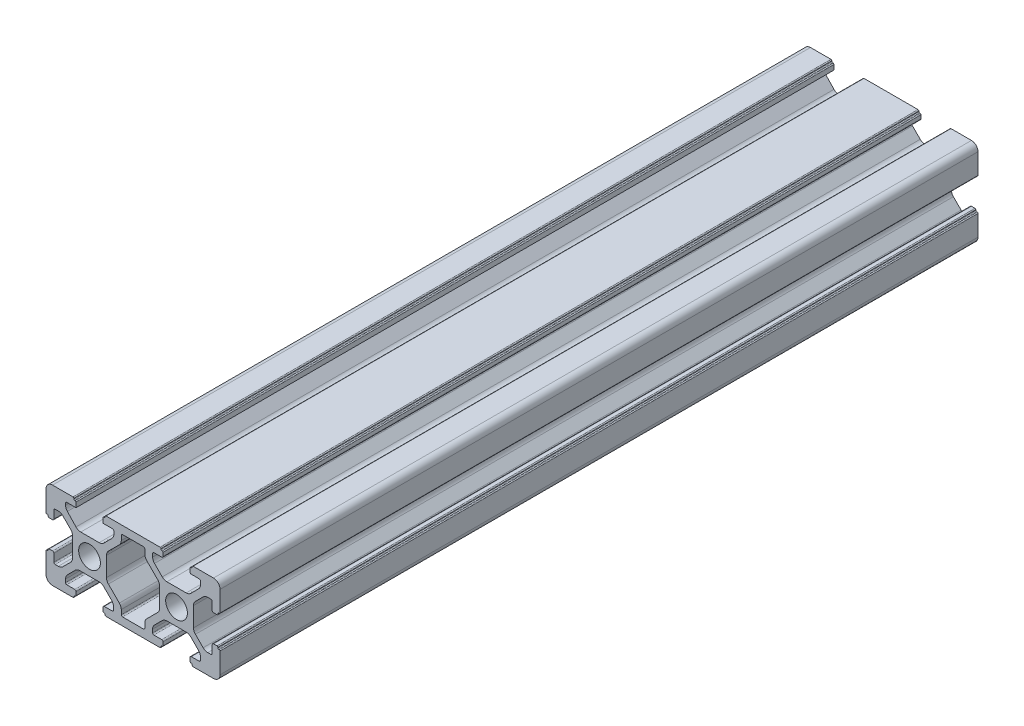
SolidWorks part; units mm, degrees
material "6063-O"
ref_plane "Front Plane" through (0, 0, 0) normal (0, 0, 1) x (1, 0, 0)
ref_plane "Top Plane" through (0, 0, 0) normal (0, 1, 0) x (1, 0, 0)
ref_plane "Right Plane" through (0, 0, 0) normal (1, 0, 0) x (0, 0, -1)
sketch "Sketch1" plane through (0, 0, 0) normal (0, 0, 1) x (1, 0, 0)
  line L0 (1.5, 0) -> (6.2, 0)
  line L1 (40, 1.5) -> (40, 6.2)
  line L2 (38.5, 20) -> (33.8, 20)
  line L3 (0, 18.5) -> (0, 13.8)
  line L4 (17.6, 1.8) -> (22.4, 1.8)
  line L5 (32.218, 13.9) -> (27.782, 13.9)
  line L6 (26.1, 12.218) -> (26.1, 7.782)
  line L7 (17.6, 18.2) -> (22.4, 18.2)
  line L8 (12.218, 13.9) -> (7.9864, 13.9)
  line L9 (6.1, 12.218) -> (6.1, 7.782)
  line L10 (7.782, 6.1) -> (12.218, 6.1)
  line L11 (13.9, 7.782) -> (13.9, 12.218)
  line L12 (27.782, 6.1) -> (32.218, 6.1)
  line L13 (33.9, 7.782) -> (33.9, 12.218)
  line L14 (26.7213, 14.3393) -> (24.9393, 16.1213)
  line L15 (33.2787, 14.3393) -> (35.0607, 16.1213)
  line L16 (34.3393, 13.2787) -> (36.1213, 15.0607)
  line L17 (25.6607, 6.7213) -> (23.1393, 4.2)
  line L18 (15.2, 1.8) -> (13.4, 1.8)
  line L19 (26.7213, 5.6607) -> (24.9393, 3.8787)
  line L20 (24.8, 1.8) -> (26.6, 1.8)
  line L21 (15.3, 18.2) -> (13.1, 18.2)
  line L22 (13.2787, 14.3393) -> (15.1607, 16.2213)
  line L23 (14.3393, 13.2787) -> (16.8607, 15.8)
  line L24 (5.6607, 6.7213) -> (3.8787, 4.9393)
  line L25 (6.7213, 5.6607) -> (4.9393, 3.8787)
  line L26 (6.897, 14.3689) -> (4.9106, 16.4674)
  line L27 (5.6607, 13.2787) -> (3.8787, 15.0607)
  line L28 (14.3393, 6.7213) -> (16.8607, 4.2)
  line L29 (13.2787, 5.6607) -> (15.0607, 3.8787)
  line L30 (24.8, 18.2) -> (26.6, 18.2)
  line L31 (25.6607, 13.2787) -> (23.1393, 15.8)
  line L32 (34.3393, 6.7213) -> (36.1213, 4.9393)
  line L33 (33.2787, 5.6607) -> (35.0607, 3.8787)
  line L34 (1.8, 15.2) -> (1.8, 13.4)
  line L35 (24.5, 2.1) -> (24.5, 2.818)
  line L36 (4.5, 2.1) -> (4.5, 2.818)
  line L37 (2.818, 4.5) -> (2.1, 4.5)
  line L38 (4.5, 17.9) -> (4.5, 17.4986)
  line L39 (2.818, 15.5) -> (2.1, 15.5)
  line L40 (15.6, 17.9) -> (15.6, 17.282)
  line L41 (15.5, 2.818) -> (15.5, 2.1)
  line L42 (38.2, 15.2) -> (38.2, 13.4)
  line L43 (35.5, 2.818) -> (35.5, 2.1)
  line L44 (37.182, 4.5) -> (37.9, 4.5)
  line L45 (35.5, 17.182) -> (35.5, 17.9)
  line L46 (37.182, 15.5) -> (37.9, 15.5)
  line L47 (17.3, 2.1) -> (17.3, 3.1393)
  line L48 (22.7, 2.1) -> (22.7, 3.1393)
  line L49 (17.3, 17.9) -> (17.3, 16.8607)
  line L50 (22.7, 17.9) -> (22.7, 16.8607)
  line L51 (24.5, 17.9) -> (24.5, 17.182)
  line L52 (6.9, 19.3) -> (6.9, 18.2)
  line L53 (13.1, 19.3) -> (13.1, 18.2)
  line L54 (6.9, 1.5) -> (6.9, 0.7)
  line L55 (13.1, 1.5) -> (13.1, 0.7)
  line L56 (13.8, 0) -> (26.2, 0)
  line L57 (6.6, 1.8) -> (4.8, 1.8)
  line L58 (6.9, 18.2) -> (4.8, 18.2)
  line L59 (6.2, 20) -> (1.5, 20)
  line L60 (39.3, 6.9) -> (38.5, 6.9)
  line L61 (39.3, 13.1) -> (38.5, 13.1)
  line L62 (1.5, 13.1) -> (0.7, 13.1)
  line L63 (1.5, 6.9) -> (0.7, 6.9)
  line L64 (0, 6.2) -> (0, 1.5)
  line L65 (1.8, 6.6) -> (1.8, 4.8)
  line L66 (38.2, 6.6) -> (38.2, 4.8)
  line L67 (40, 13.8) -> (40, 18.5)
  line L68 (33.1, 19.3) -> (33.1, 18.5)
  line L69 (26.9, 19.3) -> (26.9, 18.5)
  line L70 (26.9, 1.5) -> (26.9, 0.7)
  line L71 (33.1, 1.5) -> (33.1, 0.7)
  line L72 (33.8, 0) -> (38.5, 0)
  line L73 (33.4, 1.8) -> (35.2, 1.8)
  line L74 (26.2, 20) -> (13.8, 20)
  line L75 (33.4, 18.2) -> (35.2, 18.2)
  line L76 (6.7, 0.5) -> (6.6, 0.5)
  line L77 (6.4, 0.3) -> (6.4, 0.2)
  line L78 (13.3, 0.5) -> (13.4, 0.5)
  line L79 (13.6, 0.3) -> (13.6, 0.2)
  line L80 (26.7, 0.5) -> (26.6, 0.5)
  line L81 (26.4, 0.3) -> (26.4, 0.2)
  line L82 (33.3, 0.5) -> (33.4, 0.5)
  line L83 (33.6, 0.3) -> (33.6, 0.2)
  line L85 (6.4, 19.8) -> (6.4, 19.7)
  line L86 (6.6, 19.5) -> (6.7, 19.5)
  line L87 (13.6, 19.8) -> (13.6, 19.7)
  line L88 (13.4, 19.5) -> (13.3, 19.5)
  line L89 (26.4, 19.8) -> (26.4, 19.7)
  line L90 (26.6, 19.5) -> (26.7, 19.5)
  line L91 (33.6, 19.8) -> (33.6, 19.7)
  line L92 (33.4, 19.5) -> (33.3, 19.5)
  line L93 (0.5, 13.3) -> (0.5, 13.4)
  line L94 (0.3, 13.6) -> (0.2, 13.6)
  line L95 (0.5, 6.7) -> (0.5, 6.6)
  line L96 (0.3, 6.4) -> (0.2, 6.4)
  line L97 (39.5, 13.3) -> (39.5, 13.4)
  line L98 (39.7, 13.6) -> (39.8, 13.6)
  line L99 (39.5, 6.7) -> (39.5, 6.6)
  line L100 (39.7, 6.4) -> (39.8, 6.4)
  circle A0 centre (10, 10) radius 2.5
  circle A1 centre (30, 10) radius 2.5
  arc A2 (38.5, 0) -> (40, 1.5) centre (38.5, 1.5) ccw
  arc A3 (40, 18.5) -> (38.5, 20) centre (38.5, 18.5) ccw
  arc A4 (1.5, 0) -> (0, 1.5) centre (1.5, 1.5) cw
  arc A5 (1.5, 20) -> (0, 18.5) centre (1.5, 18.5) ccw
  arc A6 (26.7213, 5.6607) -> (27.782, 6.1) centre (27.782, 4.6) cw
  arc A7 (32.218, 6.1) -> (33.2787, 5.6607) centre (32.218, 4.6) cw
  arc A8 (33.9, 7.782) -> (34.3393, 6.7213) centre (35.4, 7.782) ccw
  arc A9 (33.2787, 14.3393) -> (32.218, 13.9) centre (32.218, 15.4) cw
  arc A10 (14.3393, 6.7213) -> (13.9, 7.782) centre (15.4, 7.782) cw
  arc A11 (14.3393, 13.2787) -> (13.9, 12.218) centre (15.4, 12.218) ccw
  arc A12 (25.6607, 6.7213) -> (26.1, 7.782) centre (24.6, 7.782) ccw
  arc A13 (26.1, 12.218) -> (25.6607, 13.2787) centre (24.6, 12.218) ccw
  arc A14 (27.782, 13.9) -> (26.7213, 14.3393) centre (27.782, 15.4) cw
  arc A15 (5.6607, 13.2787) -> (6.1, 12.218) centre (4.6, 12.218) cw
  arc A16 (5.6607, 6.7213) -> (6.1, 7.782) centre (4.6, 7.782) ccw
  arc A17 (13.2787, 5.6607) -> (12.218, 6.1) centre (12.218, 4.6) ccw
  arc A18 (6.7213, 5.6607) -> (7.782, 6.1) centre (7.782, 4.6) cw
  arc A19 (13.2787, 14.3393) -> (12.218, 13.9) centre (12.218, 15.4) cw
  arc A20 (6.897, 14.3689) -> (7.9864, 13.9) centre (7.9864, 15.4) ccw
  arc A21 (36.1213, 4.9393) -> (37.182, 4.5) centre (37.182, 6) ccw
  arc A22 (36.1213, 15.0607) -> (37.182, 15.5) centre (37.182, 14) cw
  arc A23 (35.0607, 16.1213) -> (35.5, 17.182) centre (34, 17.182) ccw
  arc A24 (24.5, 17.182) -> (24.9393, 16.1213) centre (26, 17.182) ccw
  arc A25 (22.7, 16.8607) -> (23.1393, 15.8) centre (24.2, 16.8607) ccw
  arc A26 (17.3, 16.8607) -> (16.8607, 15.8) centre (15.8, 16.8607) cw
  arc A27 (4.9106, 16.4674) -> (4.5, 17.4986) centre (6, 17.4986) cw
  arc A28 (15.6, 17.282) -> (15.1607, 16.2213) centre (14.1, 17.282) cw
  arc A29 (3.8787, 15.0607) -> (2.818, 15.5) centre (2.818, 14) ccw
  arc A30 (3.8787, 4.9393) -> (2.818, 4.5) centre (2.818, 6) cw
  arc A31 (4.9393, 3.8787) -> (4.5, 2.818) centre (6, 2.818) ccw
  arc A32 (35.0607, 3.8787) -> (35.5, 2.818) centre (34, 2.818) cw
  arc A33 (24.9393, 3.8787) -> (24.5, 2.818) centre (26, 2.818) ccw
  arc A34 (22.7, 3.1393) -> (23.1393, 4.2) centre (24.2, 3.1393) cw
  arc A35 (17.3, 3.1393) -> (16.8607, 4.2) centre (15.8, 3.1393) ccw
  arc A36 (15.5, 2.818) -> (15.0607, 3.8787) centre (14, 2.818) ccw
  arc A37 (1.8, 6.6) -> (1.5, 6.9) centre (1.5, 6.6) ccw
  arc A38 (1.8, 13.4) -> (1.5, 13.1) centre (1.5, 13.4) cw
  arc A39 (17.6, 18.2) -> (17.3, 17.9) centre (17.6, 17.9) ccw
  arc A40 (22.4, 1.8) -> (22.7, 2.1) centre (22.4, 2.1) ccw
  arc A41 (17.6, 1.8) -> (17.3, 2.1) centre (17.6, 2.1) cw
  arc A42 (15.2, 1.8) -> (15.5, 2.1) centre (15.2, 2.1) ccw
  arc A43 (6.6, 1.8) -> (6.9, 1.5) centre (6.6, 1.5) cw
  arc A44 (13.4, 1.8) -> (13.1, 1.5) centre (13.4, 1.5) ccw
  arc A45 (24.8, 1.8) -> (24.5, 2.1) centre (24.8, 2.1) cw
  arc A46 (35.2, 1.8) -> (35.5, 2.1) centre (35.2, 2.1) ccw
  arc A47 (26.6, 1.8) -> (26.9, 1.5) centre (26.6, 1.5) cw
  arc A48 (33.4, 1.8) -> (33.1, 1.5) centre (33.4, 1.5) ccw
  arc A49 (26.9, 18.5) -> (26.6, 18.2) centre (26.6, 18.5) cw
  arc A50 (33.1, 18.5) -> (33.4, 18.2) centre (33.4, 18.5) ccw
  arc A51 (37.9, 4.5) -> (38.2, 4.8) centre (37.9, 4.8) ccw
  arc A52 (38.5, 13.1) -> (38.2, 13.4) centre (38.5, 13.4) cw
  arc A53 (38.5, 6.9) -> (38.2, 6.6) centre (38.5, 6.6) ccw
  arc A54 (38.2, 15.2) -> (37.9, 15.5) centre (37.9, 15.2) ccw
  arc A55 (35.2, 18.2) -> (35.5, 17.9) centre (35.2, 17.9) cw
  arc A56 (24.8, 18.2) -> (24.5, 17.9) centre (24.8, 17.9) ccw
  arc A57 (22.4, 18.2) -> (22.7, 17.9) centre (22.4, 17.9) cw
  arc A58 (15.3, 18.2) -> (15.6, 17.9) centre (15.3, 17.9) cw
  arc A59 (4.5, 17.9) -> (4.8, 18.2) centre (4.8, 17.9) cw
  arc A60 (1.8, 15.2) -> (2.1, 15.5) centre (2.1, 15.2) cw
  arc A61 (1.8, 4.8) -> (2.1, 4.5) centre (2.1, 4.8) ccw
  arc A62 (4.5, 2.1) -> (4.8, 1.8) centre (4.8, 2.1) ccw
  arc A63 (34.3393, 13.2787) -> (33.9, 12.218) centre (35.4, 12.218) ccw
  arc A64 (6.4, 0.2) -> (6.2, 0) centre (6.2, 0.2) cw
  arc A65 (6.6, 0.5) -> (6.4, 0.3) centre (6.6, 0.3) ccw
  arc A66 (6.7, 0.5) -> (6.9, 0.7) centre (6.7, 0.7) ccw
  arc A67 (13.6, 0.2) -> (13.8, 0) centre (13.8, 0.2) ccw
  arc A68 (13.4, 0.5) -> (13.6, 0.3) centre (13.4, 0.3) cw
  arc A69 (13.3, 0.5) -> (13.1, 0.7) centre (13.3, 0.7) cw
  arc A70 (26.4, 0.2) -> (26.2, 0) centre (26.2, 0.2) cw
  arc A71 (26.6, 0.5) -> (26.4, 0.3) centre (26.6, 0.3) ccw
  arc A72 (26.7, 0.5) -> (26.9, 0.7) centre (26.7, 0.7) ccw
  arc A73 (33.6, 0.2) -> (33.8, 0) centre (33.8, 0.2) ccw
  arc A74 (33.4, 0.5) -> (33.6, 0.3) centre (33.4, 0.3) cw
  arc A75 (33.3, 0.5) -> (33.1, 0.7) centre (33.3, 0.7) cw
  arc A76 (39.8, 6.4) -> (40, 6.2) centre (39.8, 6.2) cw
  arc A77 (39.5, 6.6) -> (39.7, 6.4) centre (39.7, 6.6) ccw
  arc A78 (39.5, 6.7) -> (39.3, 6.9) centre (39.3, 6.7) ccw
  arc A79 (39.5, 13.3) -> (39.3, 13.1) centre (39.3, 13.3) cw
  arc A80 (39.5, 13.4) -> (39.7, 13.6) centre (39.7, 13.4) cw
  arc A81 (39.8, 13.6) -> (40, 13.8) centre (39.8, 13.8) ccw
  arc A82 (33.3, 19.5) -> (33.1, 19.3) centre (33.3, 19.3) ccw
  arc A83 (33.6, 19.7) -> (33.4, 19.5) centre (33.4, 19.7) cw
  arc A84 (33.6, 19.8) -> (33.8, 20) centre (33.8, 19.8) cw
  arc A85 (26.7, 19.5) -> (26.9, 19.3) centre (26.7, 19.3) cw
  arc A86 (26.4, 19.7) -> (26.6, 19.5) centre (26.6, 19.7) ccw
  arc A87 (26.4, 19.8) -> (26.2, 20) centre (26.2, 19.8) ccw
  arc A88 (0.2, 6.4) -> (0, 6.2) centre (0.2, 6.2) ccw
  arc A89 (0.5, 6.6) -> (0.3, 6.4) centre (0.3, 6.6) cw
  arc A90 (0.5, 6.7) -> (0.7, 6.9) centre (0.7, 6.7) cw
  arc A91 (13.3, 19.5) -> (13.1, 19.3) centre (13.3, 19.3) ccw
  arc A92 (13.6, 19.7) -> (13.4, 19.5) centre (13.4, 19.7) cw
  arc A93 (13.6, 19.8) -> (13.8, 20) centre (13.8, 19.8) cw
  arc A94 (6.2, 20) -> (6.4, 19.8) centre (6.2, 19.8) cw
  arc A95 (6.7, 19.5) -> (6.9, 19.3) centre (6.7, 19.3) cw
  arc A96 (6.4, 19.7) -> (6.6, 19.5) centre (6.6, 19.7) ccw
  arc A97 (0.5, 13.3) -> (0.7, 13.1) centre (0.7, 13.3) ccw
  arc A98 (0.2, 13.6) -> (0, 13.8) centre (0.2, 13.8) cw
  arc A99 (0.5, 13.4) -> (0.3, 13.6) centre (0.3, 13.4) ccw
  point P87 (0, 0)
  point P178 (1.8, 6.9)
  point P181 (1.8, 13.1)
  point P186 (22.7, 1.8)
  point P193 (6.9, 1.8)
  point P204 (33.1, 1.8)
  point P209 (33.1, 18.2)
  point P216 (38.2, 6.9)
  point P243 (6.9, 0.5)
  point P248 (13.6, 0.5)
  point P257 (26.9, 0.5)
extrude "Boss-Extrude2" add sketch "Sketch1" along normal blind 174.2 contours A57 L7 A39 L49 A26 L23 A11 L11 A10 L28 A35 L47 A41 L4 A40 L48 A34 L17 A12 L6 A13 L31 A25 L50 | A0 | A1 | L59 A5 L3 A98 L94 A99 L93 A97 L62 A38 L34 A60 L39 A29 L27 A15 L9 A16 L24 A30 L37 A61 L65 A37 L63 A90 L95 A89 L96 A88 L64 A4 L0 A64 L77 A65 L76 A66 L54 A43 L57 A62 L36 A31 L25 A18 L10 A17 L29 A36 L41 A42 L18 A44 L55 A69 L78 A68 L79 A67 L56 A70 L81 A71 L80 A72 L70 A47 L20 A45 L35 A33 L19 A6 L12 A7 L33 A32 L43 A46 L73 A48 L71 A75 L82 A74 L83 A73 L72 A2 L1 A76 L100 A77 L99 A78 L60 A53 L66 A51 L44 A21 L32 A8 L13 A63 L16 A22 L46 A54 L42 A52 L61 A79 L97 A80 L98 A81 L67 A3 L2 A84 L91 A83 L92 A82 L68 A50 L75 A55 L45 A23 L15 A9 L5 A14 L14 A24 L51 A56 L30 A49 L69 A85 L90 A86 L89 A87 L74 A93 L87 A92 L88 A91 L53 L21 A58 L40 A28 L22 A19 L8 A20 L26 A27 L38 A59 L58 L52 A95 L86 A96 L85 A94
